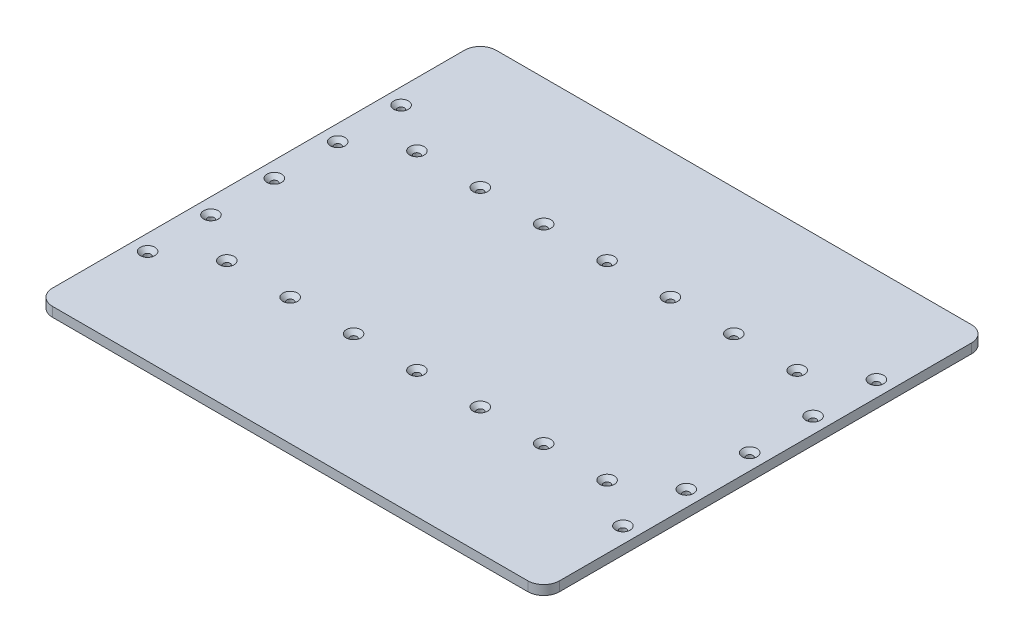
SolidWorks part; units mm, degrees
ref_plane "前视基准面" through (0, 0, 0) normal (0, 0, 1) x (1, 0, 0)
ref_plane "上视基准面" through (0, 0, 0) normal (0, 1, 0) x (1, 0, 0)
ref_plane "右视基准面" through (0, 0, 0) normal (1, 0, 0) x (0, 0, -1)
other "Configuration Table"
sketch "草图1" plane through (0, 0, 0) normal (0, 1, 0) x (1, 0, 0)
  line L1 (-150, -140) -> (150, -140)
  line L2 (-160, -130) -> (-160, 130)
  line L3 (-150, 140) -> (150, 140)
  line L4 (160, -130) -> (160, 130)
  line L5 (-160, -140) -> (-156.8729, -137.2638) construction
  line L6 (-160, 140) -> (-156.8729, 137.2638) construction
  line L8 (156.8729, 137.2638) -> (160, 140) construction
  line L9 (156.8729, -137.2638) -> (160, -140) construction
  arc A0 (150, -140) -> (160, -130) centre (150, -130) ccw
  arc A1 (-160, 130) -> (-150, 140) centre (-150, 130) cw
  arc A2 (-150, -140) -> (-160, -130) centre (-150, -130) cw
  arc A3 (150, 140) -> (160, 130) centre (150, 130) cw
  point P0 (0, 0)
  dimension "D3" = 10
  dimension "D1" = 320
  dimension "D2" = 280
extrude "凸台-拉伸1" add sketch "草图1" along normal mid plane 6
sketch "草图5" plane through (0, 3, 0) normal (0, 1, 0) x (1, 0, 0)
  line L0 (0, 0) -> (0, 142.7283) construction
  line L1 (160, 0) -> (-160, 0) construction
  line L2 (-160, 130) -> (-160, -130) construction
  line L3 (150, 140) -> (-150, 140) construction
  circle A0 centre (0, 60) radius 2.1
  circle A16 centre (40, 60) radius 2.1
  circle A17 centre (80, 60) radius 2.1
  circle A18 centre (120, 60) radius 2.1
  circle A19 centre (-120, 60) radius 2.1
  circle A20 centre (-80, 60) radius 2.1
  circle A21 centre (-40, 60) radius 2.1
  circle A22 centre (-40, -60) radius 2.1
  circle A23 centre (-80, -60) radius 2.1
  circle A24 centre (-120, -60) radius 2.1
  circle A25 centre (120, -60) radius 2.1
  circle A26 centre (80, -60) radius 2.1
  circle A27 centre (40, -60) radius 2.1
  circle A28 centre (0, -60) radius 2.1
  circle A29 centre (-150, 0) radius 2.1
  circle A30 centre (-150, -40) radius 2.1
  circle A31 centre (-150, -80) radius 2.1
  circle A32 centre (-150, 80) radius 2.1
  circle A33 centre (-150, 40) radius 2.1
  circle A34 centre (150, 40) radius 2.1
  circle A35 centre (150, 80) radius 2.1
  circle A36 centre (150, -80) radius 2.1
  circle A37 centre (150, -40) radius 2.1
  circle A38 centre (150, 0) radius 2.1
  dimension "D2" = 4.2
  dimension "D1" = 4.2
  dimension "D3" = 10
  dimension "D4" = 80
extrude "切除-拉伸4" cut sketch "草图5" against normal blind 240
chamfer "倒角2" distance 2.5 angle 45 24 edges at (150, 3, 37.9) (150, 3, 77.9) (120, 3, 57.9) (80, 3, 57.9) (40, 3, 57.9) (0, 3, 57.9) (-40, 3, 62.1) (-80, 3, 62.1) (-120, 3, 62.1) (-150, 3, 82.1) (-150, 3, 42.1) (-150, 3, 2.1) (-150, 3, -42.1) (-150, 3, -82.1) (-120, 3, -62.1) (-80, 3, -62.1) (-40, 3, -62.1) (0, 3, -57.9) (40, 3, -57.9) (150, 3, -2.1) (150, 3, -37.9) (80, 3, -57.9) (120, 3, -57.9) (150, 3, -77.9)
